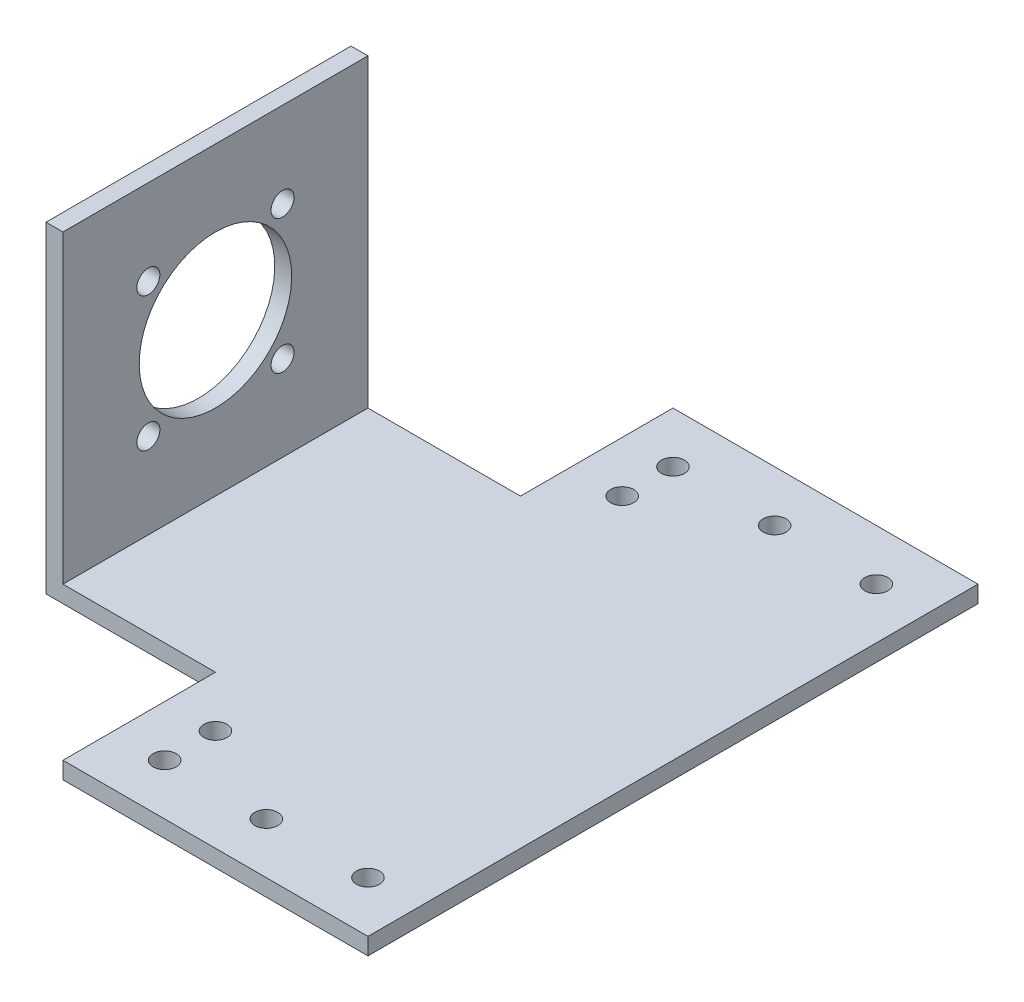
SolidWorks part; units mm, degrees
ref_plane "Vorderansicht (XY)" through (0, 0, 0) normal (0, 0, 1) x (1, 0, 0)
ref_plane "Draufansicht (XZ)" through (0, 0, 0) normal (0, 1, 0) x (1, 0, 0)
ref_plane "Seitenansicht (ZY)" through (0, 0, 0) normal (1, 0, 0) x (0, 0, -1)
sketch "Skizze1" plane through (0, 0, 0) normal (0, 0, 1) x (1, 0, 0)
  line L0 (0, 0) -> (45, 0)
  line L1 (45, 0) -> (45, 2.5)
  line L2 (45, 2.5) -> (0, 2.5)
  line L3 (0, 2.5) -> (0, 0)
  point P6 (0, 0.093)
  dimension "D1" = 45
  dimension "D2" = 2.5
extrude "Aufsatz-Linear austragen1" add sketch "Skizze1" along normal mid plane 90
sketch "Skizze2" plane through (0, 0, 0) normal (0, 0, 1) x (1, 0, 0)
  line L0 (0, 0) -> (-25, 0)
  line L1 (-25, 0) -> (-25, 47.5)
  line L2 (-25, 47.5) -> (-22.5, 47.5)
  line L3 (-22.5, 47.5) -> (-22.5, 2.5)
  line L4 (-22.5, 2.5) -> (0, 2.5)
  line L5 (0, 2.5) -> (0, 0)
  dimension "D1" = 25
  dimension "D2" = 2.5
  dimension "D3" = 45
extrude "Aufsatz-Linear austragen2" add sketch "Skizze2" along normal mid plane 45
sketch "Skizze3" plane through (-22.5, 0, 0) normal (1, 0, 0) x (0, 0, -1)
  line L0 (-22.5, 2.5) -> (-22.5, 47.5) construction
  line L1 (-22.5, 47.5) -> (22.5, 47.5) construction
  circle A0 centre (0, 25) radius 11.25
  point P5 (0, 24.9303)
  dimension "D3" = 22.5
  dimension "D1" = 22.5
  dimension "D2" = 22.5
extrude "Schnitt-Linear austragen1" cut sketch "Skizze3" against normal through all
sketch "Skizze4" plane through (-22.5, 0, 0) normal (1, 0, 0) x (0, 0, -1)
  line L0 (22.5, 25) -> (-22.5, 25) construction
  line L1 (0, 47.5) -> (0, 2.5) construction
  line L2 (-22.5, 47.5) -> (22.5, 47.5) construction
  line L3 (22.5, 2.5) -> (22.5, 47.5) construction
  line L4 (-22.5, 2.5) -> (-22.5, 47.5) construction
  line L5 (-45, 2.5) -> (45, 2.5) construction
  line L6 (-9.8995, 34.8995) -> (0, 25) construction
  circle A0 centre (-9.8995, 34.8995) radius 1.7
  circle A1 centre (9.8995, 34.8995) radius 1.7
  circle A2 centre (-9.8995, 15.1005) radius 1.7
  circle A3 centre (9.8995, 15.1005) radius 1.7
  point P21 (0, 25)
  dimension "D2" = 3.4
  dimension "D1" = 14
  dimension "D3" = 45
extrude "Schnitt-Linear austragen2" cut sketch "Skizze4" against normal through all
sketch "Skizze5" plane through (0, 2.5, 0) normal (0, 1, 0) x (1, 0, 0)
  line L0 (-33.7783, 0) -> (54.9339, 0) construction
  line L1 (45, 45) -> (0, 45) construction
  line L2 (0, 22.5) -> (-22.5, 22.5) construction
  line L3 (0, 22.5) -> (0, 45) construction
  line L4 (45, -45) -> (45, 45) construction
  circle A0 centre (7.5, 37.5) radius 1.7
  circle A1 centre (7.5, 30) radius 1.7
  circle A2 centre (22.5, 37.5) radius 1.7
  circle A3 centre (37.5, 37.5) radius 1.7
  circle A4 centre (7.5, -30) radius 1.7
  circle A5 centre (37.5, -37.5) radius 1.7
  circle A6 centre (22.5, -37.5) radius 1.7
  circle A7 centre (7.5, -37.5) radius 1.7
  point P11 (4.8794, 25.6869)
  point P12 (5.7211, 37.8633)
  point P13 (4.6549, 27.8753)
  point P14 (15.3163, 40.0517)
  point P15 (38.7152, 40.5567)
  point P22 (0, 0)
  point P23 (0, 0)
  point P24 (0, 0)
  point P25 (0, 0)
  dimension "D6" = 3.4
  dimension "D1" = 7.5
  dimension "D2" = 7.5
  dimension "D3" = 7.5
  dimension "D4" = 15
  dimension "D5" = 7.5
extrude "Schnitt-Linear austragen3" cut sketch "Skizze5" against normal through all
